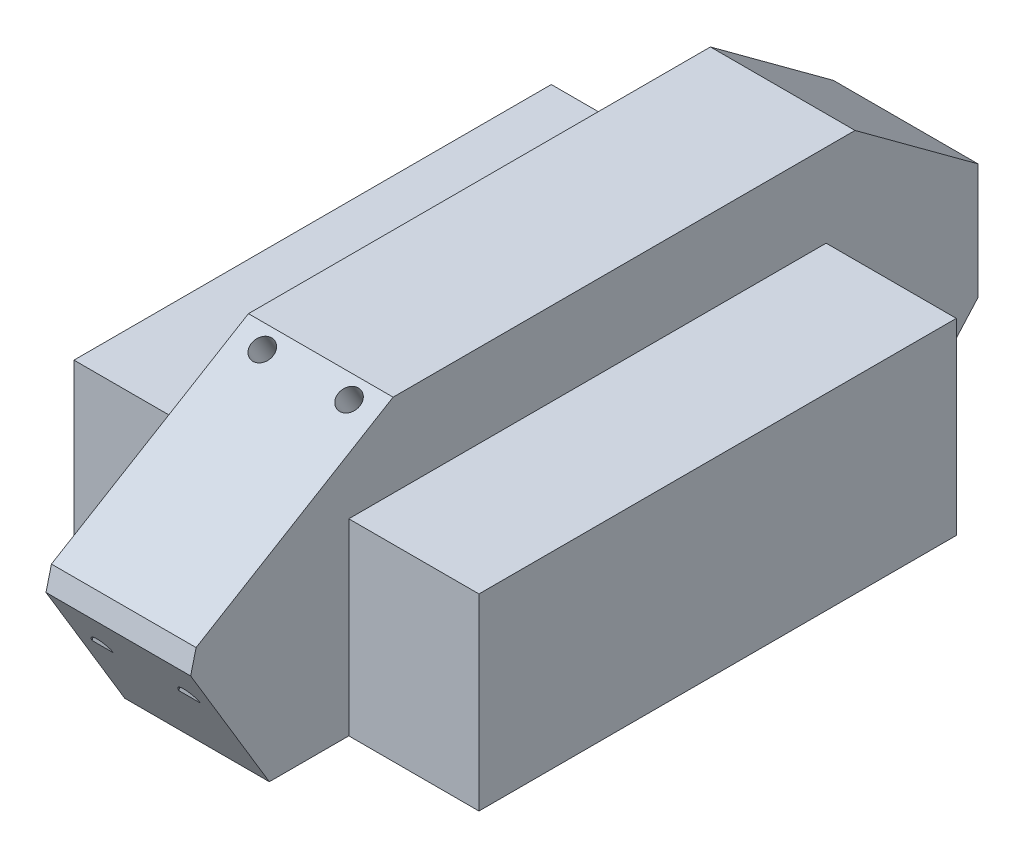
SolidWorks part; units mm, degrees
ref_plane "前视基准面" through (0, 0, 0) normal (0, 0, 1) x (1, 0, 0)
ref_plane "上视基准面" through (0, 0, 0) normal (0, 1, 0) x (1, 0, 0)
ref_plane "右视基准面" through (0, 0, 0) normal (1, 0, 0) x (0, 0, -1)
sketch "草图1" plane through (0, 0, 0) normal (0, 1, 0) x (1, 0, 0)
  line L1 (10, -55) -> (-10, -55)
  line L2 (10, -55) -> (10, 55)
  line L3 (10, 55) -> (-10, 55)
  line L4 (-10, -55) -> (-10, 55)
  line L5 (10, -55) -> (-10, 55) construction
  line L6 (10, 55) -> (-10, -55) construction
  point P0 (0, 0)
  dimension "D1" = 20
  dimension "D2" = 110
extrude "凸台-拉伸1" add sketch "草图1" along normal blind 38
sketch "草图2" plane through (0, 0, 0) normal (0, 0, 1) x (1, 0, 0)
  line L0 (10, 38) -> (10, 0) construction
  line L1 (10, 26) -> (10, 0)
  line L2 (10, 26) -> (28, 26)
  line L3 (28, 26) -> (28, 0)
  line L4 (28, 0) -> (10, 0)
  line L5 (0, 0) -> (0, 61.998) construction
  line L6 (-28, 0) -> (-10, 0)
  line L7 (-28, 26) -> (-28, 0)
  line L8 (-10, 26) -> (-28, 26)
  line L9 (-10, 26) -> (-10, 0)
  dimension "D1" = 26
  dimension "D2" = 18
extrude "凸台-拉伸4" add sketch "草图2" along normal offset from surface 23 and the other way offset from surface (34 mm away) 21 up to face at (0, 19, 55) other way up to face at (0, 19, -55)
sketch "草图7" plane through (10, 0, 0) normal (1, 0, 0) x (0, 0, -1)
  line L1 (55, 0) -> (55, 9)
  line L2 (55, 9) -> (44, 0)
  line L3 (-55, 38) -> (55, 38) construction
  line L5 (55, 38) -> (55, 0) construction
  line L8 (-55, 38) -> (-55, 0) construction
  line L11 (34, 0) -> (55, 0) construction
  line L15 (-55, 20) -> (-55, 38)
  line L16 (-55, 38) -> (-25.043, 38)
  line L17 (37, 38) -> (55, 38)
  line L18 (55, 38) -> (55, 25)
  line L20 (-25.043, 38) -> (-55, 20)
  line L21 (37, 38) -> (55, 25)
  line L22 (44, 0) -> (55, 0)
  dimension "D1" = 121
  dimension "D2" = 18
  dimension "D3" = 13
  dimension "D4" = 18
  dimension "D5" = 16
  dimension "D6" = 11
extrude "切除-拉伸1" cut sketch "草图7" against normal up to surface (20 mm away)
sketch "草图9" plane through (0, 0, 55) normal (0, 0, 1) x (1, 0, 0)
  line L0 (0, 0) -> (0, 34.7633) construction
  line L1 (-10, 0) -> (10, 0) construction
  line L2 (-10, 20) -> (10, 20) construction
  circle A0 centre (-6, 11.5) radius 1.5
  circle A1 centre (6, 11.5) radius 1.5
  dimension "D2" = 3
  dimension "D1" = 12
  dimension "D3" = 8.5
extrude "切除-拉伸3" cut sketch "草图9" against normal blind 5
sketch "草图10" plane through (10, 0, 0) normal (1, 0, 0) x (0, 0, -1)
  line L1 (58.4735, 40.5) -> (-40.802, 40.5)
  line L2 (58.4735, 40.5) -> (58.4735, 37.5)
  line L3 (58.4735, 37.5) -> (-40.802, 37.5)
  line L4 (-40.802, 40.5) -> (-40.802, 37.5)
  dimension "D1" = 3
  dimension "D2" = 17.5
extrude "切除-拉伸4" cut sketch "草图10" against normal through all
sketch "草图8" plane through (0, 38.9758, 23.419) normal (0, 0.8572, 0.515) x (1, 0, 0)
  line L0 (0, -2.8654) -> (0, -36.8434) construction
  line L2 (-10, -36.8434) -> (10, -36.8434) construction
  line L3 (-10, -2.8654) -> (10, -2.8654) construction
  circle A0 centre (-6, -5.3054) radius 1.5
  circle A1 centre (6, -5.3054) radius 1.5
  dimension "D1" = 3
  dimension "D2" = 12
  dimension "D3" = 2.44
extrude "切除-拉伸2" cut sketch "草图8" against normal blind 5
sketch "草图11" plane through (10, 0, 0) normal (1, 0, 0) x (0, 0, -1)
  line L0 (38, 37.5) -> (55, 37.5)
  line L1 (-25.8751, 37.5) -> (55, 37.5) construction
  line L2 (55, 37.5) -> (55, 25)
  line L3 (55, 37.5) -> (55, 0) construction
  line L4 (55, 25) -> (38, 37.5)
  line L5 (55, 9) -> (47, 0)
  line L6 (34, 0) -> (55, 0) construction
  line L7 (47, 0) -> (55, 0)
  line L8 (55, 0) -> (55, 9)
  line M6 (55, 0) -> (55, 37.5)
  line M7 (55, 37.5) -> (-25.8751, 37.5)
  line M14 (34, 0) -> (55, 0)
  dimension "D1" = 16
  dimension "D2" = 9
  dimension "D3" = 8
  dimension "D4" = 17
  dimension "D5" = 12.5
extrude "切除-拉伸5" cut sketch "草图11" against normal through all contours L4 M6 M7 | L5 M6 M14
sketch "草图12" plane through (10, 0, 0) normal (1, 0, 0) x (0, 0, -1)
  line L0 (-55, 20) -> (-42.9828, 0)
  line L1 (-55, 0) -> (-32, 0) construction
  line L2 (-42.9828, 0) -> (-55, 0)
  line L3 (-55, 0) -> (-55, 20)
  line L4 (-25.8751, 37.5) -> (-55, 20) construction
  dimension "D1" = 90
extrude "切除-拉伸6" cut sketch "草图12" against normal through all
chamfer "倒角1" distance 2.2 angle 45 1 edges at (0, 20, 55)
